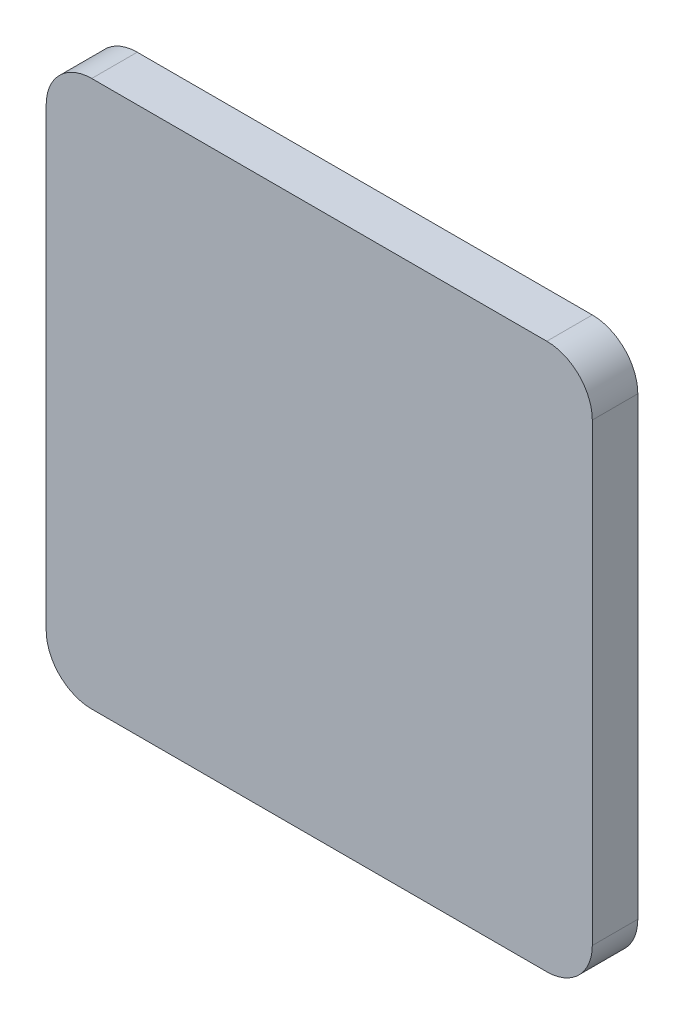
SolidWorks part; units mm, degrees
ref_plane "Front Plane" through (0, 0, 0) normal (0, 0, 1) x (1, 0, 0)
ref_plane "Top Plane" through (0, 0, 0) normal (0, 1, 0) x (1, 0, 0)
ref_plane "Right Plane" through (0, 0, 0) normal (1, 0, 0) x (0, 0, -1)
sketch "Sketch1" plane through (0, 0, 0) normal (0, 0, 1) x (1, 0, 0)
  line L1 (-50, 60) -> (50, 60)
  line L2 (-60, 50) -> (-60, -50)
  line L3 (-50, -60) -> (50, -60)
  line L4 (60, 50) -> (60, -50)
  line L5 (-60, 60) -> (60, -60) construction
  line L6 (-60, -60) -> (60, 60) construction
  arc A0 (-60, -50) -> (-50, -60) centre (-50, -50) ccw
  arc A1 (50, -60) -> (60, -50) centre (50, -50) ccw
  arc A2 (50, 60) -> (60, 50) centre (50, 50) cw
  arc A3 (-50, 60) -> (-60, 50) centre (-50, 50) ccw
  point P0 (0, 0)
  dimension "D3" = 10
  dimension "D1" = 120
  dimension "D2" = 120
extrude "Boss-Extrude1" add sketch "Sketch1" along normal blind 10 contours A3 L2 A0 L3 A1 L4 A2 L1
sketch "Sketch2" plane through (0, 0, 10) normal (0, 0, 1) x (1, 0, 0)
  line L0 (0, 0) -> (0, 40) construction
  line L1 (-50, 50) -> (50, 50) construction
  line L2 (-50, 50) -> (-50, -50) construction
  line L3 (-50, -50) -> (50, -50) construction
  line L4 (50, 50) -> (50, -50) construction
  line L5 (-50, 50) -> (50, -50) construction
  line L6 (-50, -50) -> (50, 50) construction
  line L7 (0, 40) -> (-40, 40) construction
  line L8 (-40, 40) -> (-40, 0) construction
  line L9 (-40, 0) -> (0, 0) construction
  line L11 (0, 20) -> (-20, 20) construction
  line L12 (-20, 40) -> (-20, 20) construction
  circle A0 centre (0, 40) radius 4 construction
  circle A1 centre (0, 20) radius 4 construction
  circle A2 centre (0, 0) radius 4 construction
  circle A3 centre (-20, 20) radius 4 construction
  circle A4 centre (-20, 40) radius 4 construction
  circle A5 centre (-40, 40) radius 4 construction
  circle A6 centre (0, 0) radius 4 construction
  circle A7 centre (20, 0) radius 4 construction
  circle A8 centre (40, 0) radius 4 construction
  circle A9 centre (40, 20) radius 4 construction
  circle A10 centre (40, 40) radius 4 construction
  circle A11 centre (20, 20) radius 4 construction
  circle A12 centre (0, 0) radius 4 construction
  circle A13 centre (0, -20) radius 4 construction
  circle A14 centre (0, -40) radius 4 construction
  circle A15 centre (20, -40) radius 4 construction
  circle A16 centre (40, -40) radius 4 construction
  circle A17 centre (20, -20) radius 4 construction
  circle A18 centre (0, 0) radius 4
  circle A19 centre (-20, 0) radius 4 construction
  circle A20 centre (-40, 0) radius 4 construction
  circle A21 centre (-40, -20) radius 4 construction
  circle A22 centre (-40, -40) radius 4 construction
  circle A23 centre (-20, -20) radius 4 construction
  text T0 "1" font "Century Gothic" height 100
  point P0 (0, 0)
  point P20 (0, 0)
  point P55 (0, 0)
  dimension "D4" = 8
  dimension "D1" = 100
  dimension "D2" = 100
  dimension "D3" = 40
  dimension "D5" = 4
